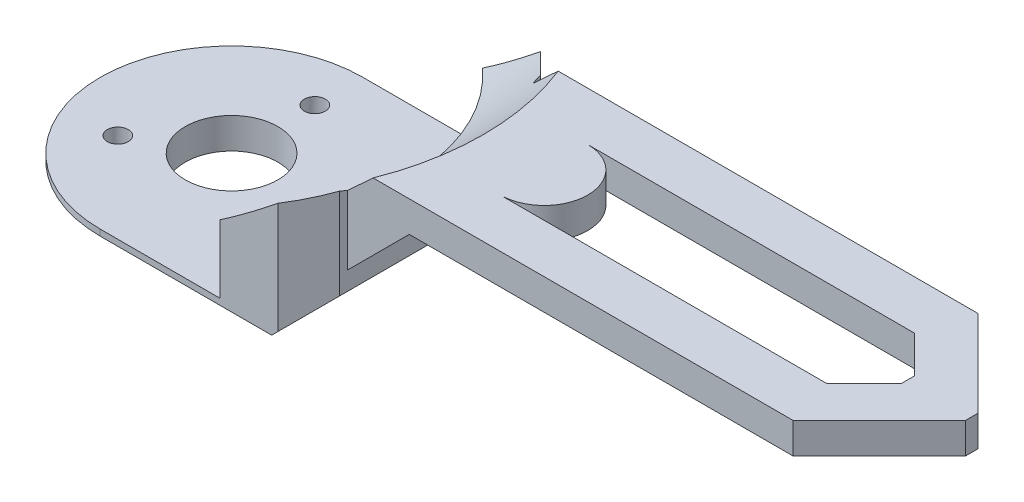
SolidWorks part; units mm, degrees
ref_plane "前视基准面" through (0, 0, 0) normal (0, 0, 1) x (1, 0, 0)
ref_plane "上视基准面" through (0, 0, 0) normal (0, 1, 0) x (1, 0, 0)
ref_plane "右视基准面" through (0, 0, 0) normal (1, 0, 0) x (0, 0, -1)
sketch "草图1" plane through (0, 0, 0) normal (0, 1, 0) x (1, 0, 0)
  line L4 (28.8, 28.8) -> (28.8, -28.8) construction
  line L5 (33.8, 21.3) -> (33.8, -21.3)
  line L7 (0, -21.3) -> (28.8, -21.3)
  line L8 (0, 21.3) -> (28.8, 21.3)
  line L10 (28.8, -21.3) -> (33.8, -21.3)
  line L11 (28.8, 21.3) -> (33.8, 21.3)
  line L12 (0, 28.8) -> (28.8, 28.8) construction
  line L13 (0, -28.8) -> (28.8, -28.8) construction
  arc A0 (0, 28.8) -> (0, -28.8) centre (0, 0) ccw construction
  circle A1 centre (0, 0) radius 13.5 construction
  circle A2 centre (0, 13.5) radius 1.7
  circle A3 centre (11.6913, -6.75) radius 1.7
  circle A4 centre (-11.6913, -6.75) radius 1.7
  circle A5 centre (0, 0) radius 7.5
  circle A6 centre (0, 0) radius 21.25 construction
  arc A7 (0, 21.3) -> (0, -21.3) centre (0, 0) ccw
  point P12 (0, 0)
  dimension "D2" = 3.4
  dimension "D3" = 27
  dimension "D4" = 57.6
  dimension "D7" = 15
  dimension "D8" = 42.5
  dimension "D5" = 28.8
  dimension "D6" = 5
  dimension "D9" = 7.5
  dimension "D1" = 3
extrude "凸台-拉伸1" add sketch "草图1" along normal blind 5
sketch "草图3" plane through (0, 5, 0) normal (0, 1, 0) x (1, 0, 0)
  line L0 (33.8, 21.3) -> (19.3843, 21.3)
  line L2 (33.8, -21.3) -> (19.3843, -21.3)
  line L4 (33.8, 21.3) -> (33.8, -21.3)
  arc A0 (19.3843, -21.3) -> (19.3843, 21.3) centre (0, 0) ccw
  dimension "D1" = 28.8
extrude "凸台-拉伸2" add sketch "草图3" along normal blind 23
sketch "草图4" plane through (33.8, 0, 0) normal (1, 0, 0) x (0, 0, -1)
  line L0 (-21.3, 28) -> (21.3, 28) construction
  line L1 (15, 28) -> (-15, 28)
  line L2 (15, 28) -> (15, 23)
  line L3 (15, 23) -> (-15, 23)
  line L4 (-15, 28) -> (-15, 23)
  dimension "D1" = 30
  dimension "D2" = 15
  dimension "D3" = 5
extrude "凸台-拉伸3" add sketch "草图4" along normal blind 86.2
chamfer "倒角1" distance 10 angle 45 1 edges at (33.8, 23, 0)
chamfer "倒角2" distance 10 angle 45 1 edges at (33.8, 0, 0)
chamfer "倒角3" distance 14 angle 45 2 edges at (120, 25.5, -15) (120, 25.5, 15)
chamfer "倒角5" distance 12 angle 45 1 edges at (28.8, 28, 0)
chamfer "倒角6" distance 5 angle 45 2 edges at (33.8, 18.5758, 21.3) (33.8, 18.5758, -21.3)
sketch "草图6" plane through (0, 28, 0) normal (0, 1, 0) x (1, 0, 0)
  line L1 (50.6526, 7.0911) -> (109.6177, 7.0911)
  line L3 (50.6526, -7.0911) -> (109.6177, -7.0911)
  line L4 (109.6177, 7.0911) -> (109.6177, -7.0911)
  arc A0 (50.6526, -7.0911) -> (50.6526, 7.0911) centre (50.6526, 0) ccw
extrude "切除-拉伸2" cut sketch "草图6" against normal blind 14
chamfer "倒角7" distance 6 angle 45 2 edges at (109.6177, 25.5, 7.0911) (109.6177, 25.5, -7.0911)
chamfer "倒角8" distance 4 angle 45 3 edges at (11.9, 0, -21.3) (11.9, 0, 21.3) (-21.3, 0, 0)
